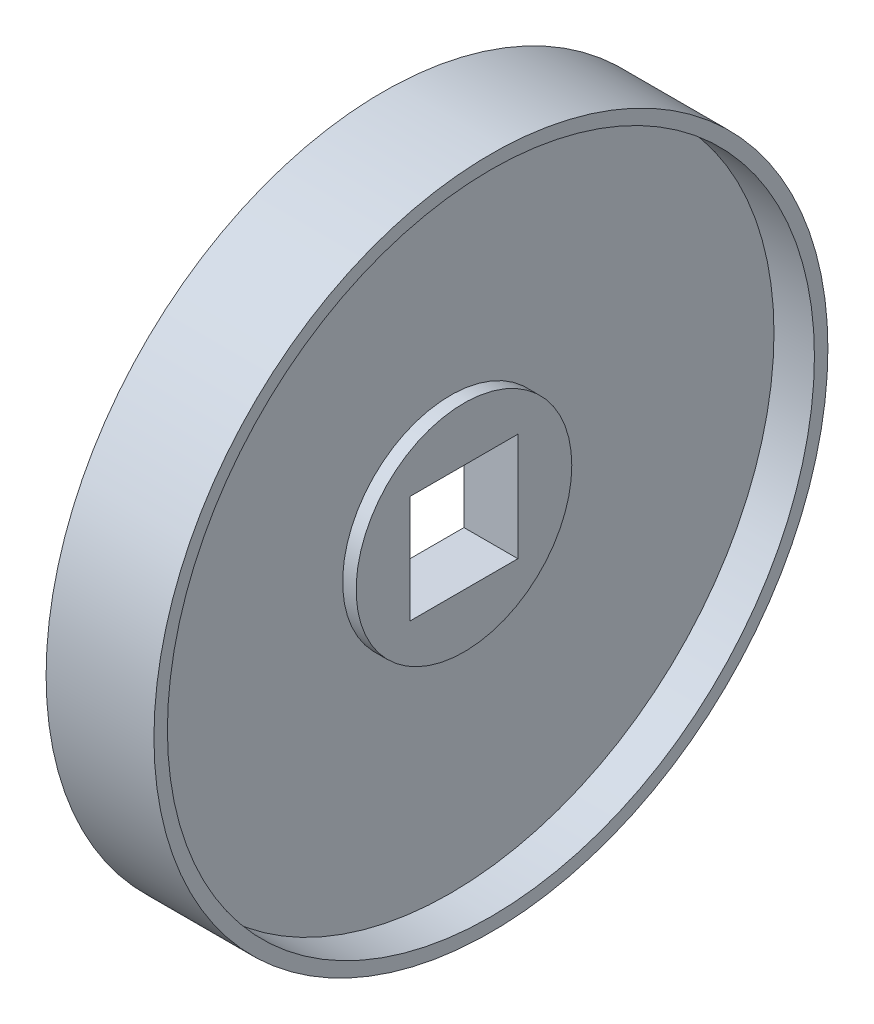
SolidWorks part; units mm, degrees
ref_plane "Front Plane" through (0, 0, 0) normal (0, 0, 1) x (1, 0, 0)
ref_plane "Top Plane" through (0, 0, 0) normal (0, 1, 0) x (1, 0, 0)
ref_plane "Right Plane" through (0, 0, 0) normal (1, 0, 0) x (0, 0, -1)
sketch "Sketch1" plane through (0, 0, 0) normal (0, 1, 0) x (1, 0, 0)
  line L1 (6.35, 0) -> (-6.35, 0)
  line L2 (6.35, 0) -> (6.35, 25.4)
  line L3 (6.35, 25.4) -> (-6.35, 25.4)
  line L4 (-6.35, 0) -> (-6.35, 25.4)
  line L5 (-3.175, 25.4) -> (3.175, 25.4)
  line L6 (-3.175, 25.4) -> (-3.175, 76.2)
  line L7 (-3.175, 76.2) -> (3.175, 76.2)
  line L8 (3.175, 25.4) -> (3.175, 76.2)
  line L9 (-12.7, 79.375) -> (12.7, 79.375)
  line L10 (-12.7, 79.375) -> (-12.7, 76.2)
  line L11 (-12.7, 76.2) -> (12.7, 76.2)
  line L12 (12.7, 79.375) -> (12.7, 76.2)
  point P8 (38.9266, 163.2871)
  point P9 (0, 25.4)
  point P10 (0, 25.4)
  point P15 (0, 76.2)
  point P16 (0, 76.2)
  point P17 (0, 0)
  dimension "D1" = 25.4
  dimension "D2" = 76.2
  dimension "D3" = 3.175
  dimension "D4" = 25.4
  dimension "D5" = 6.35
  dimension "D6" = 12.7
revolve "Revolve1" add sketch "Sketch1" angle 360 about L1
sketch "Sketch2" plane through (6.35, 0, 0) normal (1, 0, 0) x (0, 0, -1)
  line L1 (-12.7, -12.7) -> (12.7, -12.7)
  line L2 (-12.7, -12.7) -> (-12.7, 12.7)
  line L3 (-12.7, 12.7) -> (12.7, 12.7)
  line L4 (12.7, -12.7) -> (12.7, 12.7)
  line L5 (-12.7, -12.7) -> (12.7, 12.7) construction
  line L6 (-12.7, 12.7) -> (12.7, -12.7) construction
  point P0 (0, 0)
  dimension "D1" = 25.4
extrude "Cut-Extrude1" cut sketch "Sketch2" against normal through all both and the other way through all
